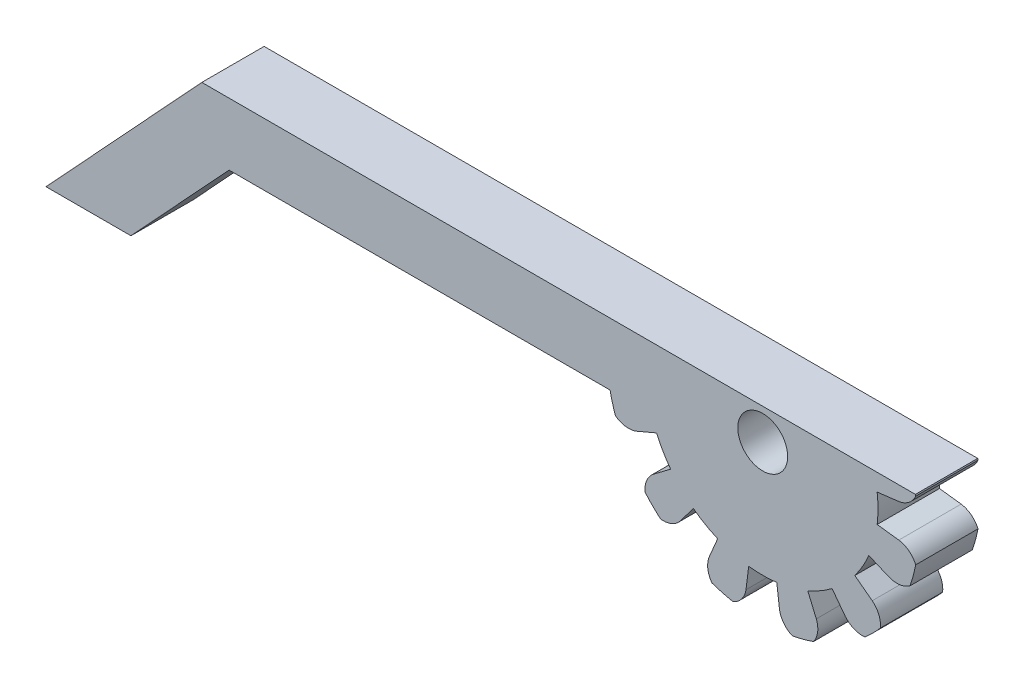
SolidWorks part; units mm, degrees
ref_plane "Ön Düzlem" through (0, 0, 0) normal (0, 0, 1) x (1, 0, 0)
ref_plane "Üst Düzlem" through (0, 0, 0) normal (0, 1, 0) x (1, 0, 0)
ref_plane "Sağ Düzlem" through (0, 0, 0) normal (1, 0, 0) x (0, 0, -1)
sketch "Sketch1" plane through (0, 0, 0) normal (0, 0, 1) x (1, 0, 0)
  line L0 (0, 149.9634) -> (17.8115, 149.9634)
  line L1 (17.8115, 149.9634) -> (24.4949, 149.9634)
  line L6 (0, 144.9634) -> (0, 149.9634) construction
  line L7 (0, 144.9634) -> (-7.2285, 161.9928) construction
  line L10 (0, 144.9634) -> (-8.1392, 168.6014) construction
  line L11 (0, 144.9634) -> (-8.5961, 165.2146) construction
  line L15 (0, 144.9634) -> (-8.1392, 168.6014) construction
  line L16 (0, 144.9634) -> (-12.876, 166.3926) construction
  line L17 (0, 144.9634) -> (-9.7683, 167.9761) construction
  line L20 (-5.694, 166.2138) -> (-6.4705, 169.1116) construction
  line L21 (-3.8823, 159.4523) -> (-5.694, 166.2138) construction
  line L24 (0, 144.9634) -> (-3.8823, 159.4523) construction
  line L25 (7.2285, 161.9928) -> (8.5961, 165.2146)
  line L28 (2.2546, 163.3255) -> (2.6811, 166.7995)
  line L29 (14.7748, 156.097) -> (17.57, 158.2034)
  line L32 (11.1336, 159.7382) -> (13.2399, 162.5334)
  line L33 (18.3621, 147.218) -> (21.836, 147.6446)
  line L36 (17.0293, 152.192) -> (20.2511, 153.5595)
  line L37 (17.0293, 137.7349) -> (20.2511, 136.3674)
  line L40 (18.3621, 142.7089) -> (21.836, 142.2823)
  line L41 (11.1336, 130.1887) -> (13.2399, 127.3935)
  line L44 (14.7748, 133.8299) -> (17.57, 131.7235)
  line L45 (2.2546, 126.6013) -> (2.6811, 123.1274)
  line L48 (7.2285, 127.9341) -> (8.5961, 124.7123)
  line L49 (-7.2285, 127.9341) -> (-8.5961, 124.7123)
  line L52 (-2.2546, 126.6013) -> (-2.6811, 123.1274)
  line L53 (-14.7748, 133.8299) -> (-17.57, 131.7235)
  line L56 (-11.1336, 130.1887) -> (-13.2399, 127.3935)
  line L57 (-18.3621, 142.7089) -> (-21.836, 142.2823)
  line L60 (-17.0293, 137.7349) -> (-20.2511, 136.3674)
  line L61 (-17.0293, 152.192) -> (-20.2511, 153.5595)
  line L62 (-18.3621, 147.218) -> (-21.836, 147.6446)
  line L63 (-11.1336, 159.7382) -> (-13.2399, 162.5334)
  line L64 (-14.7748, 156.097) -> (-17.57, 158.2034)
  line L65 (-2.2546, 163.3255) -> (-2.6811, 166.7995)
  line L66 (-7.2285, 161.9928) -> (-8.5961, 165.2146)
  line L67 (0, 144.9634) -> (0, 139.9634) construction
  line L68 (0, 149.9634) -> (-90, 149.9634)
  line L71 (0, 144.9634) -> (0, 115.9634) construction
  line L72 (0, 122.9634) -> (-115, 122.9634) construction
  line L73 (-90, 149.9634) -> (-115, 122.9634)
  line L81 (-85.6308, 139.9634) -> (-101.3716, 122.9634)
  line L82 (0, 139.9634) -> (-85.6308, 139.9634)
  line L83 (-115, 122.9634) -> (-101.3716, 122.9634)
  circle A65 centre (0, 144.9634) radius 18.5 construction
  circle A66 centre (0, 144.9634) radius 22 construction
  circle A67 centre (0, 144.9634) radius 15 construction
  circle A68 centre (0, 144.9634) radius 25 construction
  circle A69 centre (0, 144.9634) radius 18.5
  arc A70 (4.7702, 169.5041) -> (8.1392, 168.6014) centre (0, 144.9634) cw
  arc A71 (4.7702, 169.5041) -> (2.6811, 166.7995) centre (6.1535, 166.2765) ccw
  arc A72 (8.1392, 168.6014) -> (8.5961, 165.2146) centre (5.3274, 166.4979) cw
  arc A73 (-0.3229, 163.4606) -> (2.2546, 163.3255) centre (0, 144.9634) cw
  arc A74 (9.5282, 160.821) -> (7.2285, 161.9928) centre (0, 144.9634) ccw
  arc A75 (16.4015, 163.8312) -> (18.8677, 161.3649) centre (0, 144.9634) cw
  arc A76 (16.4015, 163.8312) -> (13.2399, 162.5334) centre (15.9856, 160.3443) ccw
  arc A77 (18.8677, 161.3649) -> (17.57, 158.2034) centre (15.3809, 160.9491) cw
  arc A78 (8.969, 161.1439) -> (11.1336, 159.7382) centre (0, 144.9634) cw
  arc A79 (16.1805, 153.9324) -> (14.7748, 156.097) centre (0, 144.9634) ccw
  arc A80 (23.638, 153.1026) -> (24.5407, 149.7337) centre (0, 144.9634) cw
  arc A81 (23.638, 153.1026) -> (20.2511, 153.5595) centre (21.5344, 150.2909) ccw
  arc A82 (24.5407, 149.7337) -> (21.836, 147.6446) centre (21.3131, 151.117) cw
  arc A83 (15.8576, 154.4916) -> (17.0293, 152.192) centre (0, 144.9634) cw
  arc A84 (18.4972, 144.6406) -> (18.3621, 147.218) centre (0, 144.9634) ccw
  arc A85 (24.5407, 140.1932) -> (23.638, 136.8242) centre (0, 144.9634) cw
  arc A86 (24.5407, 140.1932) -> (21.836, 142.2823) centre (21.3131, 138.8099) ccw
  arc A87 (23.638, 136.8242) -> (20.2511, 136.3674) centre (21.5344, 139.636) cw
  arc A88 (18.4972, 145.2863) -> (18.3621, 142.7089) centre (0, 144.9634) cw
  arc A89 (15.8576, 135.4352) -> (17.0293, 137.7349) centre (0, 144.9634) ccw
  arc A90 (18.8677, 128.562) -> (16.4015, 126.0957) centre (0, 144.9634) cw
  arc A91 (18.8677, 128.562) -> (17.57, 131.7235) centre (15.3809, 128.9778) ccw
  arc A92 (16.4015, 126.0957) -> (13.2399, 127.3935) centre (15.9856, 129.5825) cw
  arc A93 (16.1805, 135.9945) -> (14.7748, 133.8299) centre (0, 144.9634) cw
  arc A94 (8.969, 128.783) -> (11.1336, 130.1887) centre (0, 144.9634) ccw
  arc A95 (8.1392, 121.3255) -> (4.7702, 120.4228) centre (0, 144.9634) cw
  arc A96 (8.1392, 121.3255) -> (8.5961, 124.7123) centre (5.3274, 123.429) ccw
  arc A97 (4.7702, 120.4228) -> (2.6811, 123.1274) centre (6.1535, 123.6504) cw
  arc A98 (9.5282, 129.1058) -> (7.2285, 127.9341) centre (0, 144.9634) cw
  arc A99 (-0.3229, 126.4663) -> (2.2546, 126.6013) centre (0, 144.9634) ccw
  arc A100 (-4.7702, 120.4228) -> (-8.1392, 121.3255) centre (0, 144.9634) cw
  arc A101 (-4.7702, 120.4228) -> (-2.6811, 123.1274) centre (-6.1535, 123.6504) ccw
  arc A102 (-8.1392, 121.3255) -> (-8.5961, 124.7123) centre (-5.3274, 123.429) cw
  arc A103 (0.3229, 126.4663) -> (-2.2546, 126.6013) centre (0, 144.9634) cw
  arc A104 (-9.5282, 129.1058) -> (-7.2285, 127.9341) centre (0, 144.9634) ccw
  arc A105 (-16.4015, 126.0957) -> (-18.8677, 128.562) centre (0, 144.9634) cw
  arc A106 (-16.4015, 126.0957) -> (-13.2399, 127.3935) centre (-15.9856, 129.5825) ccw
  arc A107 (-18.8677, 128.562) -> (-17.57, 131.7235) centre (-15.3809, 128.9778) cw
  arc A108 (-8.969, 128.783) -> (-11.1336, 130.1887) centre (0, 144.9634) cw
  arc A109 (-16.1805, 135.9945) -> (-14.7748, 133.8299) centre (0, 144.9634) ccw
  arc A110 (-23.638, 136.8242) -> (-24.5407, 140.1932) centre (0, 144.9634) cw
  arc A111 (-23.638, 136.8242) -> (-20.2511, 136.3674) centre (-21.5344, 139.636) ccw
  arc A112 (-24.5407, 140.1932) -> (-21.836, 142.2823) centre (-21.3131, 138.8099) cw
  arc A113 (-15.8576, 135.4352) -> (-17.0293, 137.7349) centre (0, 144.9634) cw
  arc A114 (-18.4972, 145.2863) -> (-18.3621, 142.7089) centre (0, 144.9634) ccw
  arc A115 (-24.5407, 149.7337) -> (-23.638, 153.1026) centre (0, 144.9634) cw
  arc A116 (-24.5407, 149.7337) -> (-21.836, 147.6446) centre (-21.3131, 151.117) ccw
  arc A117 (-23.638, 153.1026) -> (-20.2511, 153.5595) centre (-21.5344, 150.2909) cw
  arc A118 (-18.4972, 144.6406) -> (-18.3621, 147.218) centre (0, 144.9634) cw
  arc A119 (-15.8576, 154.4916) -> (-17.0293, 152.192) centre (0, 144.9634) ccw
  arc A120 (-18.8677, 161.3649) -> (-16.4015, 163.8312) centre (0, 144.9634) cw
  arc A121 (-18.8677, 161.3649) -> (-17.57, 158.2034) centre (-15.3809, 160.9491) ccw
  arc A122 (-16.4015, 163.8312) -> (-13.2399, 162.5334) centre (-15.9856, 160.3443) cw
  arc A123 (-16.1805, 153.9324) -> (-14.7748, 156.097) centre (0, 144.9634) cw
  arc A124 (-8.969, 161.1439) -> (-11.1336, 159.7382) centre (0, 144.9634) ccw
  arc A125 (0.3229, 163.4606) -> (-2.2546, 163.3255) centre (0, 144.9634) ccw
  arc A126 (-4.7702, 169.5041) -> (-2.6811, 166.7995) centre (-6.1535, 166.2765) cw
  arc A127 (-8.1392, 168.6014) -> (-4.7702, 169.5041) centre (0, 144.9634) cw
  arc A128 (-8.1392, 168.6014) -> (-8.5961, 165.2146) centre (-5.3274, 166.4979) ccw
  arc A129 (-9.5282, 160.821) -> (-7.2285, 161.9928) centre (0, 144.9634) cw
  circle A130 centre (0, 144.9634) radius 4
  dimension "D10" = 30
  dimension "D11" = 37
  dimension "D12" = 44
  dimension "D15" = 4
  dimension "D16" = 4
  dimension "D13" = 50
  dimension "D18" = 3.5115
  dimension "D19" = 8
  dimension "D14" = 8
  dimension "D17" = 16
  dimension "D21" = 5
  dimension "D22" = 5
  dimension "D23" = 90
  dimension "D28" = 115
  dimension "D31" = 10
extrude "Boss-Extrude1" add sketch "Sketch1" along normal blind 10
